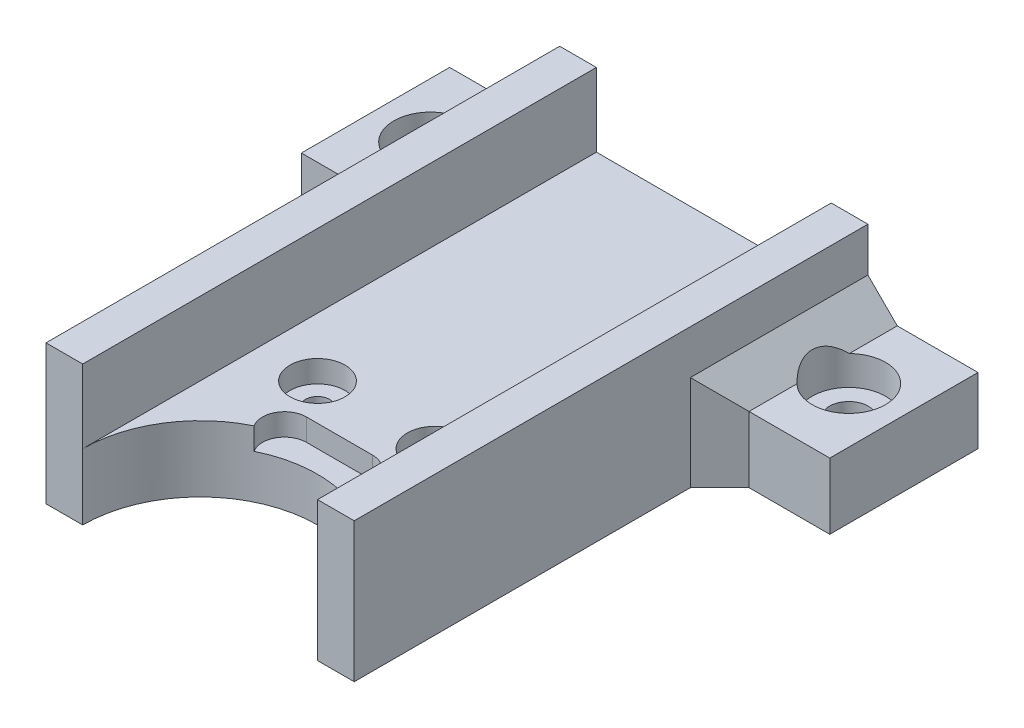
SolidWorks part; units mm, degrees
ref_plane "Front Plane" through (0, 0, 0) normal (0, 0, 1) x (1, 0, 0)
ref_plane "Top Plane" through (0, 0, 0) normal (0, 1, 0) x (1, 0, 0)
ref_plane "Right Plane" through (0, 0, 0) normal (1, 0, 0) x (0, 0, -1)
sketch "Sketch1" plane through (0, 0, 0) normal (0, 1, 0) x (1, 0, 0)
  line L0 (57, 70) -> (57, 49.8)
  line L1 (57, 49.8) -> (42, 49.8)
  line L2 (42, 49.8) -> (42, 0)
  line L3 (42, 0) -> (37, 0)
  line L4 (0, 0) -> (0, 49.8)
  line L5 (0, 70) -> (57, 70)
  line L6 (57, 59.9) -> (42, 59.9) construction
  line L7 (-15, 59.9) -> (0, 59.9) construction
  line L8 (5, 0) -> (0, 0)
  line L10 (0, 70) -> (-15, 70)
  line L12 (0, 49.8) -> (-15, 49.8)
  line L13 (-15, 70) -> (-15, 49.8)
  arc A2 (37, 0) -> (5, 0) centre (21, 0) ccw
  circle A3 centre (-7.5, 59.9) radius 2.65
  circle A4 centre (49.5, 59.9) radius 2.65
  dimension "D7" = 32
  dimension "D1" = 42
  dimension "D2" = 15
  dimension "D3" = 70
  dimension "D4" = 20.2
  dimension "D6" = 15
  dimension "D8" = 15
extrude "Boss-Extrude1" add sketch "Sketch1" along normal blind 9
sketch "Sketch2" plane through (0, 9, 0) normal (0, 1, 0) x (1, 0, 0)
  line L0 (57, 70) -> (-15, 70) construction
  line L9 (0, 0) -> (5, 0)
  line L10 (0, 0) -> (0, 70)
  line L11 (0, 70) -> (5, 70)
  line L12 (5, 0) -> (5, 70)
  line L14 (42, 0) -> (37, 0)
  line L15 (42, 0) -> (42, 70)
  line L16 (42, 70) -> (37, 70)
  line L17 (37, 0) -> (37, 70)
extrude "Boss-Extrude2" add sketch "Sketch2" along normal blind 10
sketch "Sketch3" plane through (0, 0, 0) normal (0, -1, 0) x (1, 0, 0)
  line L0 (5, 0) -> (37, 0) construction
  line L1 (21, 0) -> (21, -24) construction
  line L2 (13, -24) -> (29, -24) construction
  circle A0 centre (13, -24) radius 1.65
  circle A1 centre (29, -24) radius 1.65
  point P9 (21, -24)
  dimension "D1" = 24
  dimension "D2" = 16
extrude "Cut-Extrude1" cut sketch "Sketch3" against normal blind 10
sketch "Sketch4" plane through (0, 9, 0) normal (0, 1, 0) x (1, 0, 0)
  circle A0 centre (13, 24) radius 3.75
  circle A1 centre (29, 24) radius 3.75
extrude "Cut-Extrude2" cut sketch "Sketch4" against normal blind 3
sketch "Sketch5" plane through (0, 9, 0) normal (0, 1, 0) x (1, 0, 0)
  line L0 (16.5, 16) -> (25.5, 16) construction
  line L1 (16.5, 19) -> (25.5, 19)
  line L2 (16.5, 13) -> (25.5, 13)
  arc A0 (37, 0) -> (5, 0) centre (21, 0) ccw construction
  arc A1 (16.5, 19) -> (16.5, 13) centre (16.5, 16) ccw
  arc A2 (25.5, 13) -> (25.5, 19) centre (25.5, 16) ccw
  point P5 (21, 16)
  dimension "D2" = 3
  dimension "D1" = 9
extrude "Cut-Extrude3" cut sketch "Sketch5" against normal blind 3
chamfer "Chamfer1" distance 4 angle 45 4 edges at (42, 4.5, -49.8) (42, 9, -59.9) (0, 4.5, -49.8) (0, 9, -59.9)
sketch "Sketch6" plane through (0, 9, 0) normal (0, 1, 0) x (1, 0, 0)
  circle A0 centre (-7.5, 59.9) radius 5
  circle A1 centre (49.5, 59.9) radius 5
extrude "Cut-Extrude4" cut sketch "Sketch6" against normal blind 4 and the other way blind 5
